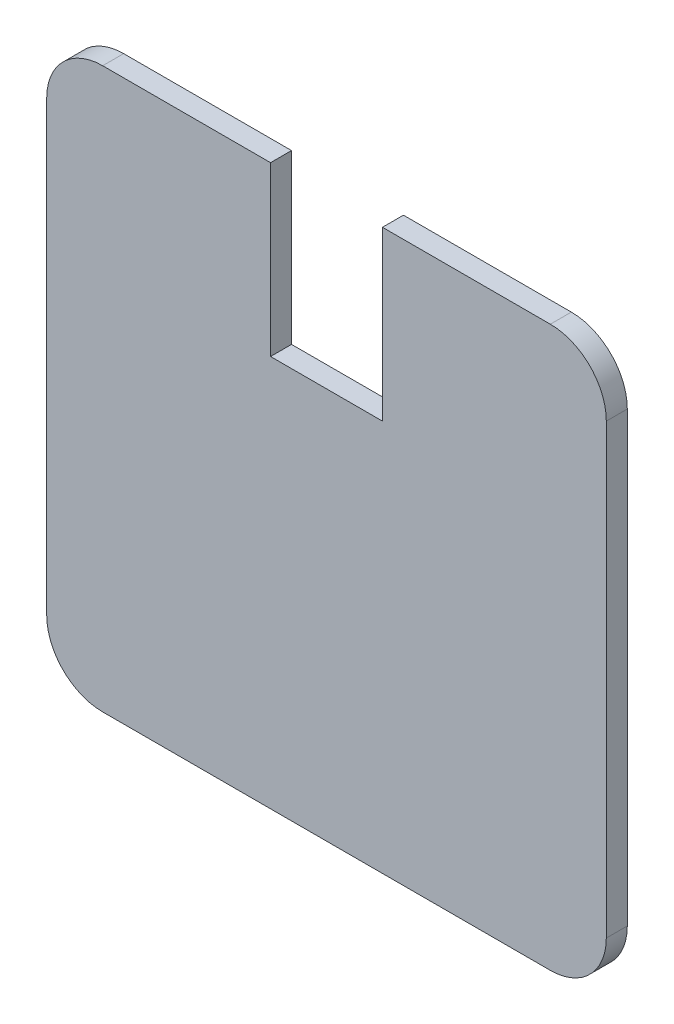
SolidWorks part; units mm, degrees
material "Polyurethane Foam Rigid"
ref_plane "Front Plane" through (0, 0, 0) normal (0, 0, 1) x (1, 0, 0)
ref_plane "Top Plane" through (0, 0, 0) normal (0, 1, 0) x (1, 0, 0)
ref_plane "Right Plane" through (0, 0, 0) normal (1, 0, 0) x (0, 0, -1)
sketch "Sketch1" plane through (0, 0, 0) normal (0, 0, 1) x (1, 0, 0)
  line L2 (-63.5, 50.8) -> (-63.5, -50.8)
  line L3 (-50.8, -63.5) -> (50.8, -63.5)
  line L4 (63.5, 50.8) -> (63.5, -50.8)
  line L5 (-12.7, 63.5) -> (12.7, 63.5) construction
  line L6 (-12.7, 63.5) -> (-12.7, 25.4)
  line L11 (50.8, 63.5) -> (12.7, 63.5)
  line L12 (-12.7, 63.5) -> (-50.8, 63.5)
  line L13 (0, 0) -> (0, 25.4) construction
  line L14 (-12.7, 25.4) -> (12.7, 25.4)
  line L15 (12.7, 25.4) -> (12.7, 63.5)
  line L16 (-59.7803, 59.7803) -> (59.7803, -59.7803) construction
  arc A0 (-63.5, -50.8) -> (-50.8, -63.5) centre (-50.8, -50.8) ccw
  arc A1 (50.8, -63.5) -> (63.5, -50.8) centre (50.8, -50.8) ccw
  arc A2 (63.5, 50.8) -> (50.8, 63.5) centre (50.8, 50.8) ccw
  arc A3 (-50.8, 63.5) -> (-63.5, 50.8) centre (-50.8, 50.8) ccw
  point P0 (0, 0)
  point P1 (0, 0)
  point P21 (59.7803, -59.7803)
  dimension "D3" = 12.7
  dimension "D1" = 127
  dimension "D5" = 25.4
  dimension "D2" = 38.1
  dimension "D4" = 127
extrude "Boss-Extrude1" add sketch "Sketch1" along normal blind 4.7625
equation "\"height\"= 8.875"
equation "\"span\"= 48"
equation "\"wing_chord\"= 9"
equation "\"fuse_len\"= 15"
equation "\"fuse_height\"= 5"
equation "\"fuse_wid\"= 5"
equation "\"D1@Sketch1\"=\"fuse_height\""
equation "\"D4@Sketch1\"=\"fuse_wid\""
